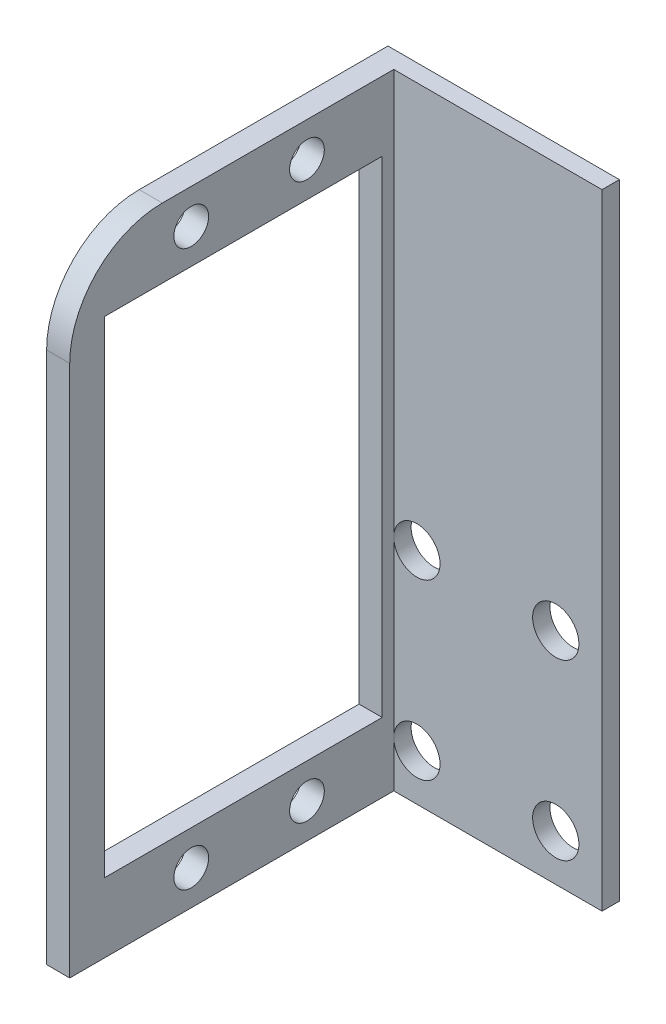
SolidWorks part; units mm, degrees
ref_plane "前视基准面" through (0, 0, 0) normal (0, 0, 1) x (1, 0, 0)
ref_plane "上视基准面" through (0, 0, 0) normal (0, 1, 0) x (1, 0, 0)
ref_plane "右视基准面" through (0, 0, 0) normal (1, 0, 0) x (0, 0, -1)
sketch "草图1" plane through (0, 0, 0) normal (1, 0, 0) x (0, 0, -1)
  line L0 (-7.5, 51) -> (-31.932, 51) construction
  line L1 (0, 0) -> (-28, 0)
  line L2 (0, 0) -> (0, 54)
  line L3 (0, 54) -> (-28, 54)
  line L4 (-28, 0) -> (-28, 54)
  line L5 (-25, 48) -> (-1, 48)
  line L6 (-25, 48) -> (-25, 6)
  line L7 (-25, 6) -> (-1, 6)
  line L8 (-1, 48) -> (-1, 6)
  line L9 (-1, 27) -> (-44.4398, 27) construction
  circle A0 centre (-7.5, 51) radius 1.5
  circle A1 centre (-17.5, 51) radius 1.5
  circle A2 centre (-7.5, 3) radius 1.5
  circle A3 centre (-17.5, 3) radius 1.5
  dimension "D7" = 3
  dimension "D8" = 3
  dimension "D9" = 10
  dimension "D10" = 6.5
  dimension "D1" = 42
  dimension "D2" = 3
  dimension "D3" = 1
  dimension "D4" = 6
  dimension "D5" = 6
  dimension "D6" = 24
  dimension "D11" = 48
extrude "凸台-拉伸1" add sketch "草图1" along normal blind 2
sketch "草图2" plane through (0, 0, 0) normal (0, 0, -1) x (-1, 0, 0)
  line L0 (-2, 0) -> (0, 0) construction
  line L1 (0, 54) -> (-20, 54)
  line L2 (0, 54) -> (0, 0)
  line L3 (0, 0) -> (-20, 0)
  line L4 (-20, 54) -> (-20, 0)
  line L5 (-16, 4) -> (9.8664, 4) construction
  line L6 (-20, 11.5) -> (7.9524, 11.5) construction
  circle A1 centre (-16, 4) radius 2
  circle A2 centre (-4, 4) radius 2
  circle A3 centre (-4, 19) radius 2
  circle A4 centre (-16, 19) radius 2
  dimension "D2" = 15
  dimension "D3" = 4
  dimension "D4" = 4
  dimension "D6" = 4
  dimension "D7" = 4
  dimension "D1" = 20
  dimension "D5" = 12
extrude "凸台-拉伸2" add sketch "草图2" along normal blind 1.5
fillet "圆角1" radius 8 1 edges at (1, 54, 28)
